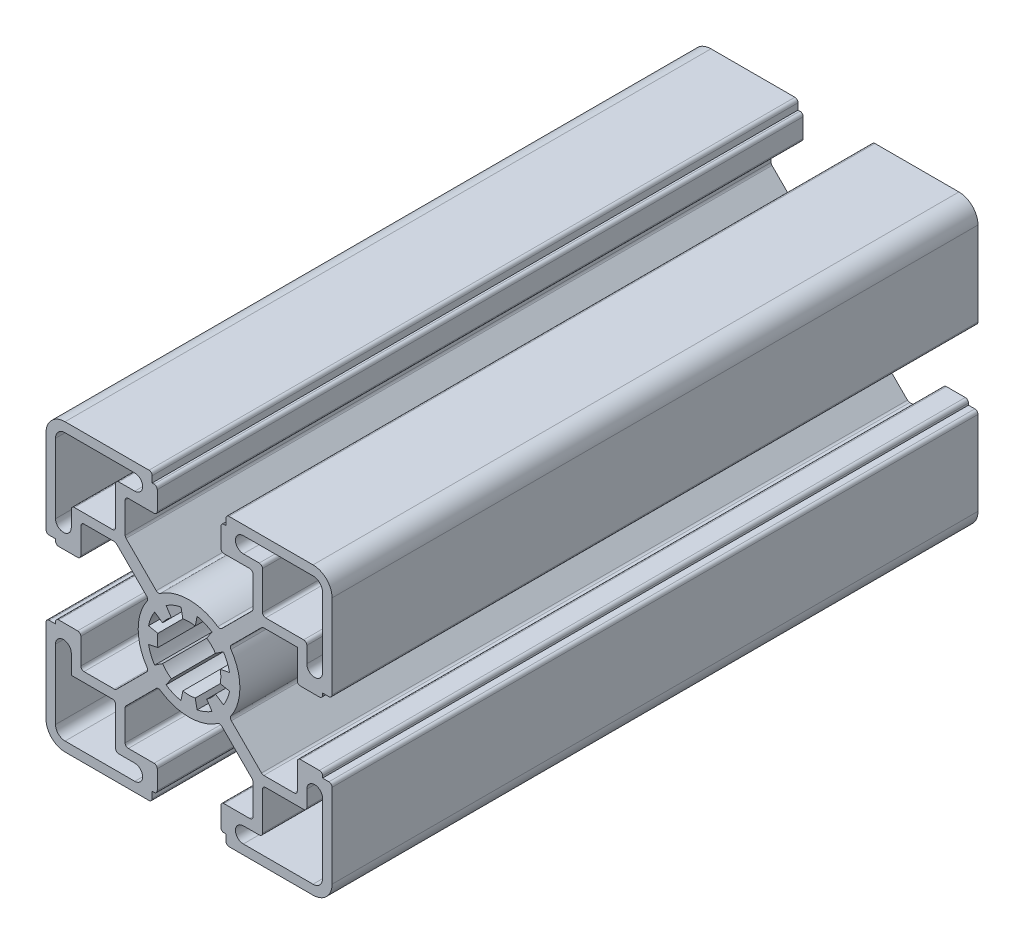
SolidWorks part; units mm, degrees
ref_plane "Front Plane" through (0, 0, 0) normal (0, 0, 1) x (1, 0, 0)
ref_plane "Top Plane" through (0, 0, 0) normal (0, 1, 0) x (1, 0, 0)
ref_plane "Right Plane" through (0, 0, 0) normal (1, 0, 0) x (0, 0, -1)
sketch "Sketch1" plane through (0, 0, 0) normal (0, 0, 1) x (1, 0, 0)
  line L0 (0, 22.5) -> (0, -22.5) construction
  line L1 (22.5, 0) -> (-22.5, 0) construction
  line L2 (-5.8, 22.5) -> (5.8, 22.5) construction
  line L3 (-5, 21) -> (5, 21) construction
  line L4 (-10.05, 10.05) -> (10.05, 10.05) construction
  line L5 (0, 0) -> (-10.05, 10.05) construction
  circle A0 centre (0, 0) radius 5 construction
  point P4 (0, 0)
  point P8 (0, 0)
  point P10 (0, 8)
  point P14 (0, 22.5)
  point P17 (0, 21)
  point P19 (0, 10.05)
sketch "Sketch2" plane through (0, 0, 0) normal (1, 0, 0) x (0, 0, -1)
  line L0 (50.8, 0) -> (-50.8, 0) construction
  point P4 (0, 0)
  dimension "D1" = 101.6
sketch "Sketch3" plane through (0, 0, 0) normal (0, 0, 1) x (1, 0, 0)
  line L5 (-21, 8.5375) -> (-21, 19.5)
  line L9 (0, 0) -> (-22.5, 22.5) construction
  line L10 (-11.55, -10.05) -> (-6.3569, -4.8569)
  line L11 (-19.5, 21) -> (-8.5375, 21)
  line L38 (-5.8, 22.5) -> (-5.8, 21)
  line L46 (-5.8, 21) -> (-5, 21)
  line L62 (-5, 21) -> (-5, 17.025)
  line L74 (-5, 17.025) -> (-10.05, 17.025)
  line L76 (-10.05, 17.025) -> (-10.05, 11.55)
  line L77 (-10.05, 11.55) -> (-4.8569, 6.3569)
  line L78 (-18.525, 8.5375) -> (-18.525, 11.55)
  line L79 (-10.05, 17.025) -> (-10.05, 22.5) construction
  line L80 (0, 22.5) -> (0, -22.5) construction
  line L81 (-5.8, 22.5) -> (5.8, 22.5) construction
  line L82 (10.05, 11.55) -> (4.8569, 6.3569)
  line L83 (10.05, 17.025) -> (10.05, 11.55)
  line L84 (5, 17.025) -> (10.05, 17.025)
  line L85 (5, 21) -> (5, 17.025)
  line L86 (5.8, 21) -> (5, 21)
  line L87 (5.8, 22.5) -> (5.8, 21)
  line L88 (-22.5, -5.8) -> (-21, -5.8)
  line L89 (-21, -5.8) -> (-21, -5)
  line L90 (-21, -5) -> (-17.025, -5)
  line L91 (-17.025, -5) -> (-17.025, -10.05)
  line L92 (-17.025, -10.05) -> (-11.55, -10.05)
  line L93 (-11.55, -10.05) -> (-6.3569, -4.8569)
  line L94 (-11.55, 10.05) -> (-6.3569, 4.8569)
  line L95 (-17.025, 10.05) -> (-11.55, 10.05)
  line L96 (-17.025, 5) -> (-17.025, 10.05)
  line L97 (-21, 5) -> (-17.025, 5)
  line L98 (-21, 5.8) -> (-21, 5)
  line L99 (-22.5, 5.8) -> (-21, 5.8)
  line L100 (-22.5, 5.8) -> (-22.5, 19.5)
  line L101 (-19.5, 22.5) -> (-5.8, 22.5)
  line L102 (-18.525, 11.55) -> (-11.55, 11.55)
  line L103 (-8.5375, 18.525) -> (-11.55, 18.525)
  line L104 (-11.55, 18.525) -> (-11.55, 11.55)
  line L108 (5.8, -22.5) -> (5.8, -21)
  line L113 (5.8, -21) -> (5, -21)
  line L117 (5.8, 22.5) -> (19.5, 22.5)
  line L118 (22.5, 19.5) -> (22.5, 5.8)
  line L119 (19.5, -22.5) -> (5.8, -22.5)
  line L120 (0, 0) -> (22.5, 0) construction
  line L121 (-22.5, -19.5) -> (-22.5, -5.8)
  line L136 (5, -21) -> (5, -17.025)
  line L137 (5, -17.025) -> (10.05, -17.025)
  line L138 (10.05, -17.025) -> (10.05, -11.55)
  line L139 (10.05, -11.55) -> (4.8569, -6.3569)
  line L140 (-10.05, -11.55) -> (-4.8569, -6.3569)
  line L141 (-10.05, -17.025) -> (-10.05, -11.55)
  line L142 (-5, -17.025) -> (-10.05, -17.025)
  line L143 (-5, -21) -> (-5, -17.025)
  line L144 (-5.8, -21) -> (-5, -21)
  line L145 (-5.8, -22.5) -> (-5.8, -21)
  line L146 (-5.8, -22.5) -> (-19.5, -22.5)
  line L147 (22.5, 5.8) -> (21, 5.8)
  line L148 (21, 5.8) -> (21, 5)
  line L149 (21, 5) -> (17.025, 5)
  line L150 (17.025, 5) -> (17.025, 10.05)
  line L151 (17.025, 10.05) -> (11.55, 10.05)
  line L152 (11.55, 10.05) -> (6.3569, 4.8569)
  line L153 (11.55, -10.05) -> (6.3569, -4.8569)
  line L154 (17.025, -10.05) -> (11.55, -10.05)
  line L155 (17.025, -5) -> (17.025, -10.05)
  line L156 (21, -5) -> (17.025, -5)
  line L157 (21, -5.8) -> (21, -5)
  line L158 (22.5, -5.8) -> (21, -5.8)
  line L159 (11.55, -10.05) -> (6.3569, -4.8569)
  line L160 (22.5, -5.8) -> (22.5, -19.5)
  line L161 (8.5375, 21) -> (19.5, 21)
  line L162 (21, 19.5) -> (21, 8.5375)
  line L163 (8.5375, 18.525) -> (11.55, 18.525)
  line L164 (11.55, 18.525) -> (11.55, 11.55)
  line L165 (18.525, 8.5375) -> (18.525, 11.55)
  line L166 (18.525, 11.55) -> (11.55, 11.55)
  line L167 (21, -8.5375) -> (21, -19.5)
  line L168 (19.5, -21) -> (8.5375, -21)
  line L169 (18.525, -8.5375) -> (18.525, -11.55)
  line L170 (18.525, -11.55) -> (11.55, -11.55)
  line L171 (8.5375, -18.525) -> (11.55, -18.525)
  line L172 (11.55, -18.525) -> (11.55, -11.55)
  line L173 (-8.5375, -21) -> (-19.5, -21)
  line L174 (-21, -19.5) -> (-21, -8.5375)
  line L175 (-8.5375, -18.525) -> (-11.55, -18.525)
  line L176 (-11.55, -18.525) -> (-11.55, -11.55)
  line L177 (-18.525, -8.5375) -> (-18.525, -11.55)
  line L178 (-18.525, -11.55) -> (-11.55, -11.55)
  line L179 (0, 0) -> (-11.55, 11.55) construction
  line L180 (0, 0) -> (11.55, 11.55) construction
  arc A2 (-21, 19.5) -> (-19.5, 21) centre (-19.5, 19.5) cw
  arc A73 (-4.8569, 6.3569) -> (4.8569, 6.3569) centre (0, 0) cw
  arc A74 (-6.3569, 4.8569) -> (-6.3569, -4.8569) centre (0, 0) ccw
  arc A75 (-19.5, 22.5) -> (-22.5, 19.5) centre (-19.5, 19.5) ccw
  arc A76 (-21, 8.5375) -> (-18.525, 8.5375) centre (-19.7625, 8.5375) ccw
  arc A77 (-8.5375, 21) -> (-8.5375, 18.525) centre (-8.5375, 19.7625) cw
  arc A80 (19.5, 22.5) -> (22.5, 19.5) centre (19.5, 19.5) cw
  arc A81 (22.5, -19.5) -> (19.5, -22.5) centre (19.5, -19.5) cw
  arc A82 (-19.5, -22.5) -> (-22.5, -19.5) centre (-19.5, -19.5) cw
  circle A88 centre (0, 0) radius 5 construction
  circle A89 centre (0, 0) radius 5
  arc A90 (-4.8569, -6.3569) -> (4.8569, -6.3569) centre (0, 0) ccw
  arc A91 (19.5, 21) -> (21, 19.5) centre (19.5, 19.5) cw
  arc A92 (6.3569, 4.8569) -> (6.3569, -4.8569) centre (0, 0) cw
  arc A93 (8.5375, 21) -> (8.5375, 18.525) centre (8.5375, 19.7625) ccw
  arc A94 (21, 8.5375) -> (18.525, 8.5375) centre (19.7625, 8.5375) cw
  arc A95 (21, -19.5) -> (19.5, -21) centre (19.5, -19.5) cw
  arc A96 (21, -8.5375) -> (18.525, -8.5375) centre (19.7625, -8.5375) ccw
  arc A97 (8.5375, -21) -> (8.5375, -18.525) centre (8.5375, -19.7625) cw
  arc A98 (-19.5, -21) -> (-21, -19.5) centre (-19.5, -19.5) cw
  arc A99 (-8.5375, -21) -> (-8.5375, -18.525) centre (-8.5375, -19.7625) ccw
  arc A100 (-21, -8.5375) -> (-18.525, -8.5375) centre (-19.7625, -8.5375) cw
  point P54 (-14.2875, 10.05)
  dimension "D2" = 3
  dimension "D3" = 1.5
  dimension "D4" = 1.5
  dimension "D5" = 1.5
  dimension "D6" = 90
  dimension "D1" = 4
extrude "Boss-Extrude1" add sketch "Sketch3" along normal up to vertex (50.8 mm away) and the other way up to vertex (50.8 mm away) contours A92 L152 L151 L150 L149 L148 L147 L118 A80 L117 L87 L86 L85 L84 L83 L82 A73 L77 L76 L74 L62 L46 L38 L101 A75 L100 L99 L98 L97 L96 L95 L94 A74 L10 L92 L91 L90 L89 L88 L121 A82 L146 L145 L144 L143 L142 L141 L140 A90 L139 L138 up to point (0, 0, 50.8) other way up to point (0, 0, -50.8)
fillet "Fillet1" radius 0.5 58 edges at (5, 21, 0) (5.8, 22.5, 0) (-5.8, 22.5, 0) (-5, 21, 0) (-10.05, 17.025, 0) (-5, 17.025, 0) (5, 17.025, 0) (-22.5, -5.8, 0) (-21, -5, 0) (-17.025, -5, 0) (-17.025, -10.05, 0) (-11.55, -10.05, 0) (-6.3569, -4.8569, 0) (-6.3569, 4.8569, 0) (-11.55, 10.05, 0) (-17.025, 10.05, 0) (-17.025, 5, 0) (-22.5, 5.8, 0) (-21, 5, 0) (-18.525, 11.55, 0) (-11.55, 11.55, 0) (-11.55, 18.525, 0) (4.8569, 6.3569, 0) (-4.8569, 6.3569, 0) (-10.05, 11.55, 0) (10.05, 17.025, 0) (10.05, 11.55, 0) (22.5, -5.8, 0) (21, -5, 0) (17.025, -5, 0) (17.025, -10.05, 0) (6.3569, 4.8569, 0) (11.55, 10.05, 0) (22.5, 5.8, 0) (21, 5, 0) (17.025, 5, 0) (4.8569, -6.3569, 0) (11.55, -11.55, 0) (-11.55, -11.55, 0) (18.525, -11.55, 0) (11.55, -18.525, 0) (10.05, -17.025, 0) (5, -17.025, 0) (5, -21, 0) (5.8, -22.5, 0) (-5.8, -22.5, 0) (-5, -21, 0) (-5, -17.025, 0) (-10.05, -17.025, 0) (-11.55, -18.525, 0) (11.55, 18.525, 0) (18.525, 11.55, 0) (11.55, 11.55, 0) (11.55, -10.05, 0) (6.3569, -4.8569, 0) (-4.8569, -6.3569, 0) (10.05, -11.55, 0) (-10.05, -11.55, 0)
sketch "Sketch4" plane through (0, 0, 50.8) normal (0, 0, 1) x (1, 0, 0)
  line L0 (-1.2681, 6.3751) -> (-0.9755, 4.9039)
  line L1 (0, 0) -> (0, 8) construction
  line L2 (-3.6112, 5.4046) -> (-2.7779, 4.1573)
  line L3 (1.2681, 6.3751) -> (0.9755, 4.9039)
  line L4 (3.6112, 5.4046) -> (2.7779, 4.1573)
  line L5 (5.4046, 3.6112) -> (4.1573, 2.7779)
  line L6 (6.3751, 1.2681) -> (4.9039, 0.9755)
  line L7 (6.3751, -1.2681) -> (4.9039, -0.9755)
  line L8 (5.4046, -3.6112) -> (4.1573, -2.7779)
  line L9 (3.6112, -5.4046) -> (2.7779, -4.1573)
  line L10 (1.2681, -6.3751) -> (0.9755, -4.9039)
  line L11 (-1.2681, -6.3751) -> (-0.9755, -4.9039)
  line L12 (-3.6112, -5.4046) -> (-2.7779, -4.1573)
  line L13 (-5.4046, -3.6112) -> (-4.1573, -2.7779)
  line L14 (-6.3751, -1.2681) -> (-4.9039, -0.9755)
  line L15 (-6.3751, 1.2681) -> (-4.9039, 0.9755)
  line L16 (-5.4046, 3.6112) -> (-4.1573, 2.7779)
  line L17 (0, 0) -> (-0.9755, 4.9039) construction
  line L18 (0, 0) -> (2.7779, 4.1573) construction
  arc A0 (-1.2681, 6.3751) -> (-3.6112, 5.4046) centre (0, 0) ccw
  circle A1 centre (0, 0) radius 5 construction
  arc A2 (-0.9755, 4.9039) -> (-2.7779, 4.1573) centre (0, 0) ccw
  arc A4 (2.7779, 4.1573) -> (0.9755, 4.9039) centre (0, 0) ccw
  arc A5 (3.6112, 5.4046) -> (1.2681, 6.3751) centre (0, 0) ccw
  arc A6 (4.9039, 0.9755) -> (4.1573, 2.7779) centre (0, 0) ccw
  arc A7 (6.3751, 1.2681) -> (5.4046, 3.6112) centre (0, 0) ccw
  arc A8 (4.1573, -2.7779) -> (4.9039, -0.9755) centre (0, 0) ccw
  arc A9 (5.4046, -3.6112) -> (6.3751, -1.2681) centre (0, 0) ccw
  arc A10 (0.9755, -4.9039) -> (2.7779, -4.1573) centre (0, 0) ccw
  arc A11 (1.2681, -6.3751) -> (3.6112, -5.4046) centre (0, 0) ccw
  arc A12 (-2.7779, -4.1573) -> (-0.9755, -4.9039) centre (0, 0) ccw
  arc A13 (-3.6112, -5.4046) -> (-1.2681, -6.3751) centre (0, 0) ccw
  arc A14 (-4.9039, -0.9755) -> (-4.1573, -2.7779) centre (0, 0) ccw
  arc A15 (-6.3751, -1.2681) -> (-5.4046, -3.6112) centre (0, 0) ccw
  arc A16 (-4.1573, 2.7779) -> (-4.9039, 0.9755) centre (0, 0) ccw
  arc A17 (-5.4046, 3.6112) -> (-6.3751, 1.2681) centre (0, 0) ccw
  dimension "D1" = 1.5
  dimension "D2" = 22.5
  dimension "D5" = 45
  dimension "D4" = 8
extrude "Cut-Extrude1" cut sketch "Sketch4" against normal through all
equation "\"D3@Sketch3\"=\"Wall@Sketch1\""
equation "\"D4@Sketch3\"=\"Wall@Sketch1\""
equation "\"D5@Sketch3\"=\"Wall@Sketch1\""
equation "\"D1@Sketch4\"=\"Wall@Sketch1\""
